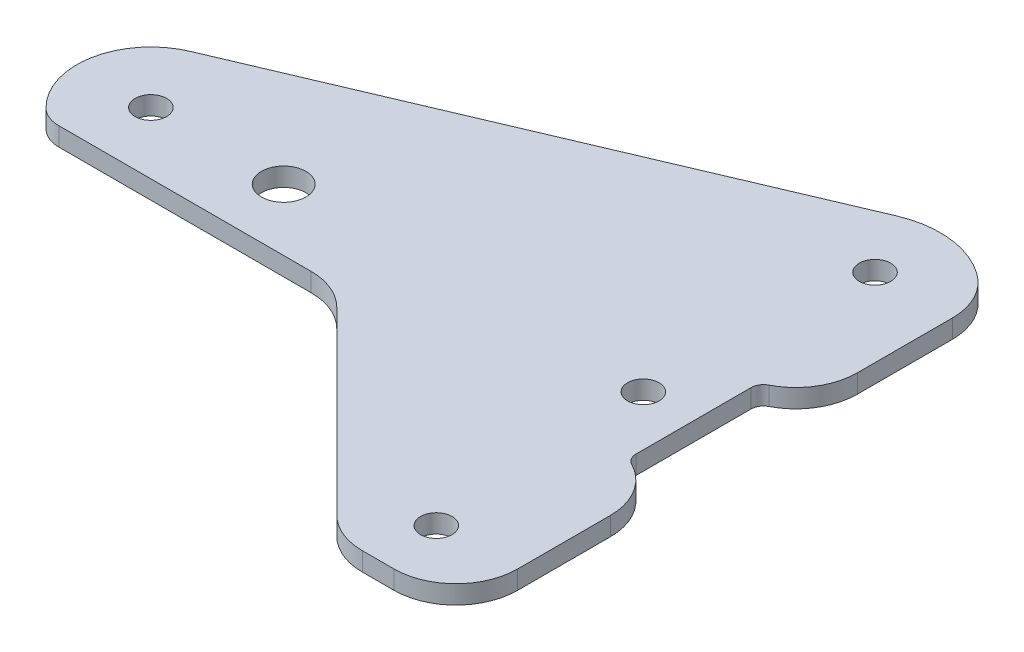
SolidWorks part; units mm, degrees
ref_plane "Alzado" through (0, 0, 0) normal (0, 0, 1) x (1, 0, 0)
ref_plane "Planta" through (0, 0, 0) normal (0, 1, 0) x (1, 0, 0)
ref_plane "Vista lateral" through (0, 0, 0) normal (1, 0, 0) x (0, 0, -1)
ref_plane "Plano1" through (0, 67.6652, 0) normal (0, -1, 0) x (1, 0, 0)
sketch "Croquis1" plane through (0, 67.6652, 0) normal (0, -1, 0) x (1, 0, 0)
  line L0 (164.3506, 56.8771) -> (123.5086, 56.8771)
  line L1 (123.7135, 35.8333) -> (203.9457, 1.7306)
  line L2 (218.4895, 3.2991) -> (218.5483, 3.3407)
  line L3 (222.7642, 11.4982) -> (222.7642, 26.8771)
  line L4 (216.2358, 37.557) -> (216.2358, 56.1971)
  line L5 (222.7642, 66.8771) -> (222.7642, 81.8771)
  line L6 (212.7642, 91.8771) -> (207.6349, 91.8771)
  line L7 (200.5638, 88.9481) -> (171.4217, 59.806)
  circle A0 centre (210.1, 82.3771) radius 2.55
  circle A1 centre (210.1, 11.3771) radius 2.55
  circle A2 centre (208.12, 46.8771) radius 2.55
  arc A3 (171.4217, 59.806) -> (164.3506, 56.8771) centre (164.3506, 66.8771) cw
  arc A4 (123.5086, 56.8771) -> (120.0094, 55.4485) centre (123.5086, 51.8771) ccw
  arc A5 (120.0094, 55.4485) -> (123.7135, 35.8333) centre (128.4076, 46.8771) ccw
  arc A6 (203.9457, 1.7306) -> (218.4895, 3.2991) centre (209.8134, 15.5353) ccw
  arc A7 (218.5483, 3.3407) -> (222.7642, 11.4982) centre (212.7642, 11.4982) ccw
  arc A8 (222.7642, 26.8771) -> (217.3239, 35.777) centre (212.7642, 26.8771) ccw
  arc A9 (217.3239, 35.777) -> (216.2358, 37.557) centre (218.2358, 37.557) cw
  arc A10 (216.2358, 56.1971) -> (217.3239, 57.9771) centre (218.2358, 56.1971) cw
  arc A11 (217.3239, 57.9771) -> (222.7642, 66.8771) centre (212.7642, 66.8771) ccw
  arc A12 (222.7642, 81.8771) -> (212.7642, 91.8771) centre (212.7642, 81.8771) ccw
  arc A13 (207.6349, 91.8771) -> (200.5638, 88.9481) centre (207.6349, 81.8771) ccw
  circle A14 centre (149.9, 46.8771) radius 3.6
  circle A15 centre (128.4076, 46.8771) radius 2.55
extrude "Saliente-Extruir1" add sketch "Croquis1" against normal blind 3
sketch "Croquis2" plane through (0, 70.6652, 0) normal (0, 1, 0) x (-1, 0, 0)
  circle A0 centre (-208.12, 46.8771) radius 2.55
extrude "Saliente-Extruir2" add sketch "Croquis2" against normal up to surface (3 mm away) up to face at (128.4076, 67.6652, 49.4271)
sketch "Croquis3" plane through (0, 70.6652, 0) normal (0, 1, 0) x (-1, 0, 0)
  circle A0 centre (-208.1076, 46.8771) radius 2.55
extrude "Cortar-Extruir1" cut sketch "Croquis3" against normal through all
